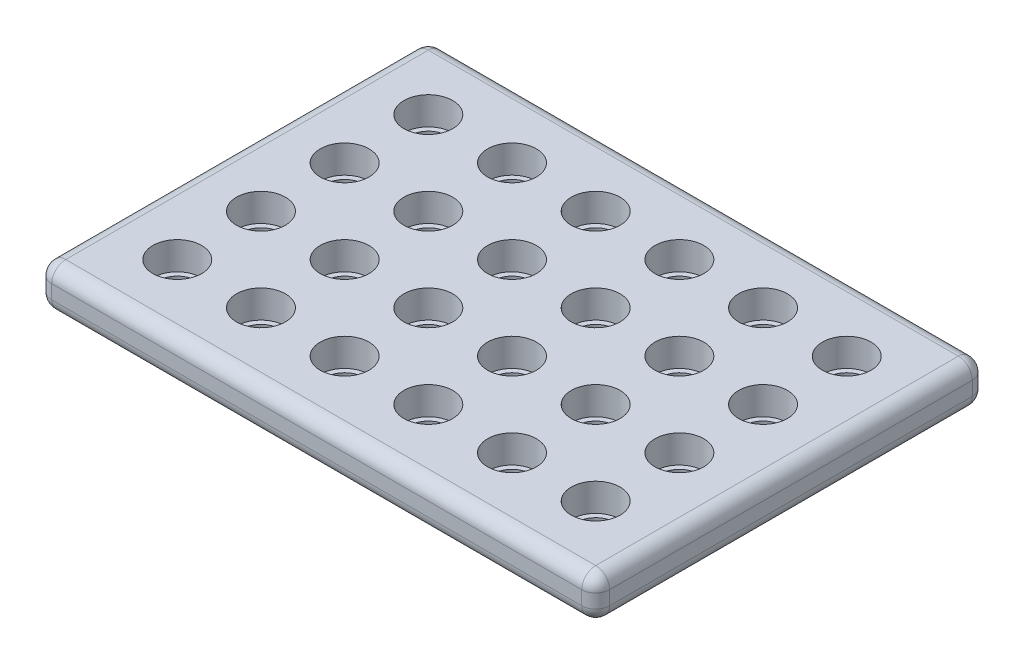
SolidWorks part; units mm, degrees
ref_plane "Front Plane" through (0, 0, 0) normal (0, 0, 1) x (1, 0, 0)
ref_plane "Top Plane" through (0, 0, 0) normal (0, 1, 0) x (1, 0, 0)
ref_plane "Right Plane" through (0, 0, 0) normal (1, 0, 0) x (0, 0, -1)
sketch "Sketch2" plane through (0, 0, 0) normal (0, 1, 0) x (1, 0, 0)
  line L1 (0, 0) -> (80, 0)
  line L2 (0, 0) -> (0, 56)
  line L3 (0, 56) -> (80, 56)
  line L4 (80, 0) -> (80, 56)
  dimension "D1" = 80
  dimension "D2" = 56
extrude "Boss-Extrude1" add sketch "Sketch2" along normal blind 6
sketch "Sketch3" plane through (0, 6, 0) normal (0, 1, 0) x (1, 0, 0)
  line L0 (0, 56) -> (0, 0) construction
  line L1 (80, 56) -> (0, 56) construction
  circle A0 centre (10, 46) radius 3.5
  dimension "D1" = 7
  dimension "D2" = 10
  dimension "D3" = 10
extrude "Cut-Extrude1" cut sketch "Sketch3" against normal blind 4
sketch "Sketch4" plane through (0, 6, 0) normal (0, 1, 0) x (1, 0, 0)
  circle A0 centre (10, 46) radius 2.75
  dimension "D1" = 5.5
extrude "Cut-Extrude2" cut sketch "Sketch4" against normal through all
pattern_linear "LPattern1" count 6 spacing 12 along (1, 0, 0) count 4 spacing 12 along (0, 0, 1) of "Cut-Extrude1", "Cut-Extrude2"
fillet "Fillet1" radius 2 12 edges at (80, 0, -28) (40, 0, 0) (0, 0, -28) (40, 0, -56) (40, 6, -56) (80, 6, -28) (0, 6, -28) (40, 6, 0) (0, 3, 0) (80, 3, 0) (80, 3, -56) (0, 3, -56)
